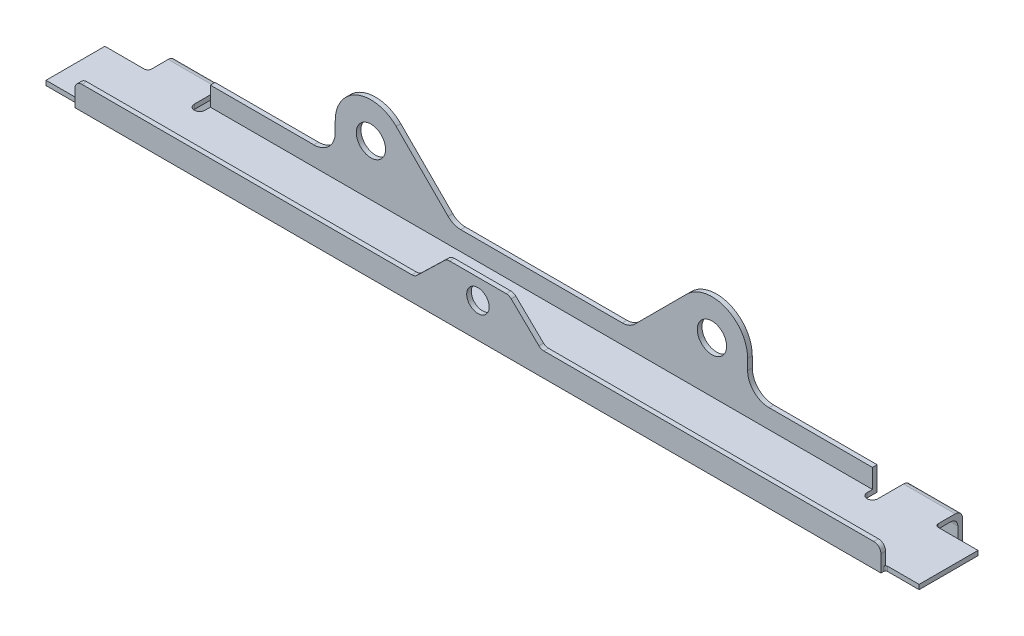
SolidWorks part; units mm, degrees
ref_plane "Front Plane" through (0, 0, 0) normal (0, 0, 1) x (1, 0, 0)
ref_plane "Top Plane" through (0, 0, 0) normal (0, 1, 0) x (1, 0, 0)
ref_plane "Right Plane" through (0, 0, 0) normal (1, 0, 0) x (0, 0, -1)
sketch "Sketch1" plane through (0, 0, 0) normal (0, 1, 0) x (1, 0, 0)
  line L0 (117.8369, 12.1285) -> (117.1861, 12.1285)
  line L1 (-143.4401, -12.1285) -> (143.4401, -12.1285)
  line L4 (155.3782, -10.4775) -> (155.3782, 10.4775)
  line L5 (155.3782, -10.4775) -> (155.3782, 10.4775)
  line L6 (155.3782, -10.4775) -> (144.2021, -10.4775)
  line L7 (143.4401, -11.2395) -> (143.4401, -12.1285)
  line L8 (140.0619, 12.1285) -> (140.0619, 20.2565)
  line L9 (155.3782, 10.4775) -> (143.4401, 10.4775)
  line L10 (143.4401, 10.4775) -> (141.332, 10.4775)
  line L11 (140.0619, 11.7475) -> (140.0619, 12.1285)
  line L16 (140.0619, 20.2565) -> (121.6469, 20.2565)
  line L17 (121.6469, 20.2565) -> (121.6469, 12.1285)
  line L18 (0, 0) -> (0, 40.6326) construction
  line L19 (117.8369, 8.5725) -> (117.8369, 12.1285)
  line L20 (-121.6469, 20.2565) -> (-121.6469, 12.1285)
  line L21 (-140.0619, 20.2565) -> (-121.6469, 20.2565)
  line L22 (-140.0619, 11.7475) -> (-140.0619, 12.1285)
  line L23 (-143.4401, 10.4775) -> (-141.332, 10.4775)
  line L24 (-155.3782, 10.4775) -> (-143.4401, 10.4775)
  line L25 (-140.0619, 12.1285) -> (-140.0619, 20.2565)
  line L26 (-143.4401, -11.2395) -> (-143.4401, -12.1285)
  line L27 (-155.3782, -10.4775) -> (-144.2021, -10.4775)
  line L28 (-155.3782, -10.4775) -> (-155.3782, 10.4775)
  line L29 (-155.3782, -10.4775) -> (-155.3782, 10.4775)
  line L30 (-117.1861, 12.1285) -> (117.1861, 12.1285)
  line L31 (-121.6469, 12.1285) -> (-121.6469, 8.5725)
  line L32 (-117.8369, 8.5725) -> (-117.8369, 12.1285)
  line L33 (-117.8369, 12.1285) -> (-117.1861, 12.1285)
  line L34 (121.6469, 12.1285) -> (121.6469, 8.5725)
  arc A1 (141.332, 10.4775) -> (140.0619, 11.7475) centre (141.3319, 11.7475) cw
  arc A2 (121.6469, 8.5725) -> (117.8369, 8.5725) centre (119.7419, 8.5725) cw
  arc A3 (143.4401, -11.2395) -> (144.2021, -10.4775) centre (144.2021, -11.2395) cw
  arc A4 (-143.4401, -11.2395) -> (-144.2021, -10.4775) centre (-144.2021, -11.2395) ccw
  arc A5 (-121.6469, 8.5725) -> (-117.8369, 8.5725) centre (-119.7419, 8.5725) ccw
  arc A6 (-141.332, 10.4775) -> (-140.0619, 11.7475) centre (-141.3319, 11.7475) ccw
  point P0 (0, 0)
  point P9 (155.3782, 1.0363)
  point P12 (155.3782, 0)
  point P22 (140.0619, 10.4775)
  point P27 (143.4401, -10.4775)
  point P50 (-143.4401, -10.4775)
  point P51 (-140.0619, 10.4775)
  point P52 (-155.3782, 0)
  point P53 (-155.3782, 1.0363)
  dimension "D7" = 1.27
  dimension "D9" = 0.762
  dimension "D11" = 3.81
  dimension "D1" = 3.3782
  dimension "D3" = 18.415
  dimension "D4" = 11.938
  dimension "D5" = 8.128
extrude "Boss-Extrude1" add sketch "Sketch1" along normal blind 1.651
sketch "Sketch2" plane through (0, 0, 0) normal (0, -1, 0) x (1, 0, 0)
  line L0 (-121.6469, -20.2565) -> (-121.6469, -8.5725) construction
  line L1 (-140.0619, -20.2565) -> (-121.6469, -20.2565)
  line L2 (-140.0619, -20.2565) -> (-140.0619, -18.6055)
  line L3 (-140.0619, -18.6055) -> (-121.6469, -18.6055)
  line L4 (-121.6469, -20.2565) -> (-121.6469, -18.6055)
  line L5 (0, 0) -> (0, -3.8993) construction
  line L6 (121.6469, -20.2565) -> (121.6469, -18.6055)
  line L7 (140.0619, -18.6055) -> (121.6469, -18.6055)
  line L8 (140.0619, -20.2565) -> (140.0619, -18.6055)
  line L9 (140.0619, -20.2565) -> (121.6469, -20.2565)
  dimension "D1" = 1.651
extrude "Boss-Extrude2" add sketch "Sketch2" along normal blind 10.287
fillet "Fillet1" radius 2.54 4 edges at (130.8544, 1.651, -20.2565) (-130.8544, 1.651, -20.2565) (130.8544, 0, -18.6055) (-130.8544, 0, -18.6055)
fillet "Fillet3" radius 1.27 4 edges at (121.6469, -10.287, -19.431) (140.0619, -10.287, -19.431) (-140.0619, -10.287, -19.431) (-121.6469, -10.287, -19.431)
sketch "Sketch4" plane through (0, 1.651, 0) normal (0, 1, 0) x (1, 0, 0)
  line L0 (-117.8369, 12.1285) -> (-117.8369, 10.4775)
  line L1 (-117.8369, 8.5725) -> (-117.8369, 12.1285) construction
  line L2 (117.8369, 12.1285) -> (117.8369, 10.4775)
  line L3 (117.8369, 8.5725) -> (117.8369, 12.1285) construction
  line L4 (117.8369, 10.4775) -> (-117.8369, 10.4775)
  line L5 (-117.8369, 12.1285) -> (117.8369, 12.1285)
  line L7 (-143.4401, -12.1285) -> (143.4401, -12.1285)
  line L8 (-143.4401, -12.1285) -> (-143.4401, -10.4775)
  line L9 (-143.4401, -10.4775) -> (143.4401, -10.4775)
  line L10 (143.4401, -12.1285) -> (143.4401, -10.4775)
  dimension "D1" = 1.651
  dimension "D2" = 1.651
  dimension "D3" = 1.651
extrude "Boss-Extrude3" add sketch "Sketch4" along normal blind 30.861
sketch "Sketch5" plane through (0, 0, 12.1285) normal (0, 0, 1) x (1, 0, 0)
  line L0 (-143.4401, 1.651) -> (143.4401, 1.651)
  line L1 (143.4401, 1.651) -> (143.4401, 8.4582)
  line L2 (143.4401, 32.512) -> (143.4401, 0) construction
  line L3 (143.4401, 8.4582) -> (22.4345, 8.4582)
  line L4 (0, 19.431) -> (0, 12.2555)
  line L6 (-143.4401, 8.4582) -> (-22.4345, 8.4582)
  line L7 (11.1125, 19.431) -> (-11.1125, 19.431)
  line L8 (-22.4345, 8.4582) -> (-11.1125, 19.431)
  line L9 (22.4345, 8.4582) -> (11.1125, 19.431)
  line L10 (-143.4401, 8.4582) -> (-143.4401, 32.512)
  line L11 (-143.4401, 32.512) -> (143.4401, 32.512)
  line L12 (143.4401, 32.512) -> (143.4401, 8.4582)
  circle A0 centre (0, 12.2555) radius 4.0005
  point P17 (0, 19.431)
  dimension "D5" = 8.001
  dimension "D1" = 6.8072
  dimension "D2" = 121.0056
  dimension "D3" = 7.1755
  dimension "D4" = 22.225
extrude "Cut-Extrude2" cut sketch "Sketch5" against normal blind 2.54
fillet "Fillet4" radius 2.54 6 edges at (143.4401, 8.4582, 11.303) (-143.4401, 8.4582, 11.303) (22.4345, 8.4582, 11.303) (11.1125, 19.431, 11.303) (-11.1125, 19.431, 11.303) (-22.4345, 8.4582, 11.303)
sketch "Sketch11" plane through (0, 0, -12.1285) normal (0, 0, -1) x (-1, 0, 0)
  line L0 (117.8369, 1.651) -> (-117.8369, 1.651)
  line L1 (-117.8369, 32.512) -> (-117.8369, 0) construction
  line L2 (-117.8369, 1.651) -> (-121.6469, 1.651) construction
  line L3 (-117.8369, 1.651) -> (-117.8369, 8.4582)
  line L4 (-140.9001, 8.4582) -> (-23.4634, 8.4582) construction
  line L6 (140.9001, 8.4582) -> (23.4634, 8.4582) construction
  line L7 (117.8369, 32.512) -> (117.8369, 0) construction
  line L8 (117.8369, 8.4582) -> (117.8369, 1.651)
  line L10 (-73.3869, 16.0782) -> (-73.3869, 19.812)
  line L11 (-117.8369, 32.512) -> (117.8369, 32.512) construction
  line L13 (-60.6869, 32.512) -> (-60.6869, 19.812)
  line L14 (0, 0) -> (0, 13.4778)
  line L17 (-81.007, 8.4582) -> (-117.8369, 8.4582)
  line L20 (60.6869, 32.512) -> (60.6869, 19.812)
  line L21 (73.3869, 19.812) -> (73.3869, 16.0782)
  line L22 (81.007, 8.4582) -> (117.8369, 8.4582)
  line L24 (-60.6869, 32.512) -> (60.6869, 32.512)
  line L25 (117.8369, 8.4582) -> (117.8369, 32.512)
  line L26 (117.8369, 32.512) -> (60.6869, 32.512)
  line L27 (-117.8369, 8.4582) -> (-117.8369, 32.512)
  line L28 (-117.8369, 32.512) -> (-60.6869, 32.512)
  line L29 (-51.7067, 28.7923) -> (-33.2325, 10.3181)
  line L30 (0, 8.4582) -> (-31.3726, 8.4582)
  line L31 (51.7067, 28.7923) -> (33.2325, 10.3181)
  line L32 (-28.7424, 8.4582) -> (28.7424, 8.4582)
  arc A0 (-51.7067, 28.7923) -> (-73.3869, 19.812) centre (-60.6869, 19.812) ccw
  circle A1 centre (-60.6869, 19.812) radius 5.207
  arc A6 (-81.007, 8.4582) -> (-73.3869, 16.0782) centre (-81.0069, 16.0782) ccw
  arc A7 (81.007, 8.4582) -> (73.3869, 16.0782) centre (81.0069, 16.0782) cw
  circle A12 centre (60.6869, 19.812) radius 5.207
  arc A13 (51.7067, 28.7923) -> (73.3869, 19.812) centre (60.6869, 19.812) cw
  arc A14 (28.7424, 8.4582) -> (33.2325, 10.3181) centre (28.7424, 14.8082) ccw
  arc A15 (-33.2325, 10.3181) -> (-28.7424, 8.4582) centre (-28.7424, 14.8082) ccw
  point P32 (-22.5869, 8.4582)
  point P37 (-22.5869, 18.8722)
  point P40 (-73.3869, 8.4582)
  point P63 (73.3869, 8.4582)
  point P64 (22.5869, 18.8722)
  point P65 (22.5869, 8.4582)
  dimension "D7" = 10.414
  dimension "D10" = 7.62
  dimension "D2" = 6.35
  dimension "D1" = 44.45
  dimension "D3" = 12.7
  dimension "D4" = 95.25
  dimension "D5" = 10.414
extrude "Cut-Extrude3" cut sketch "Sketch11" against normal blind 7.62
